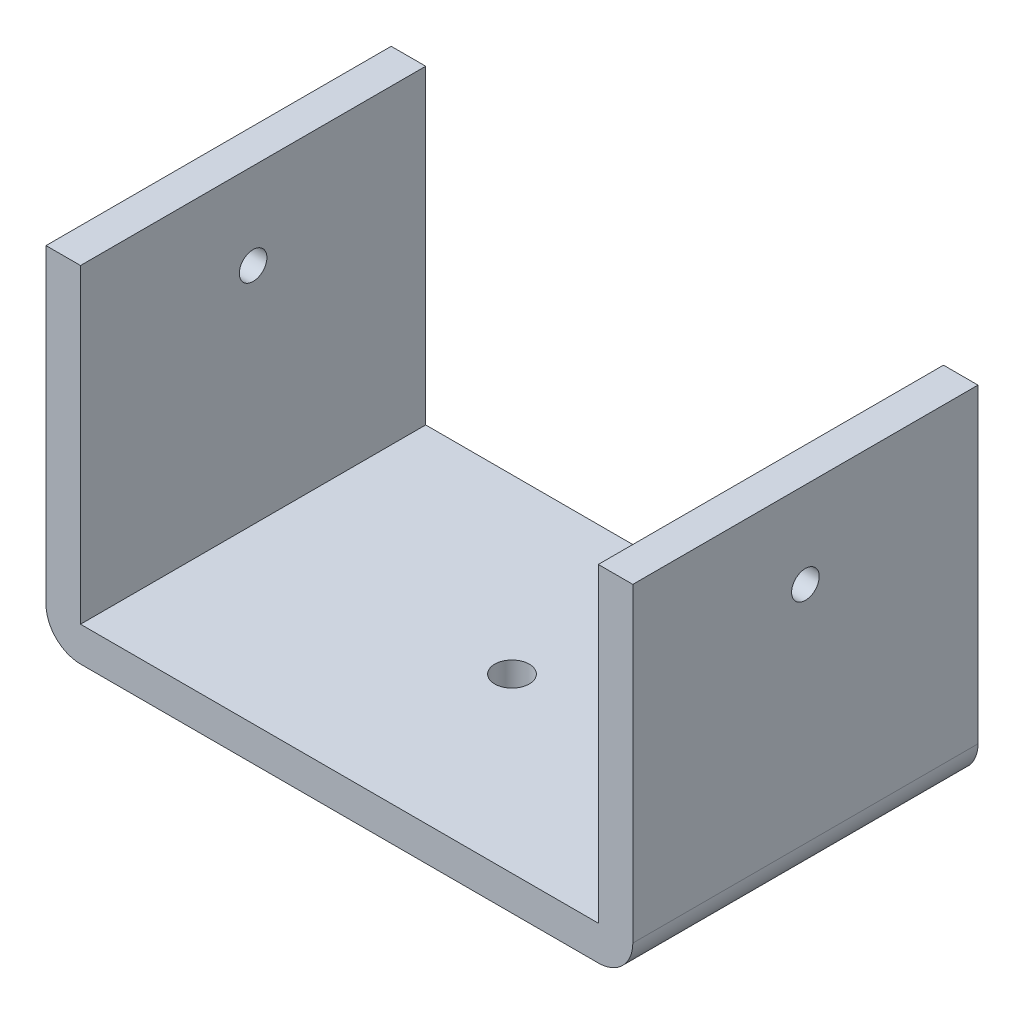
SolidWorks part; units mm, degrees
ref_plane "Front Plane" through (0, 0, 0) normal (0, 0, 1) x (1, 0, 0)
ref_plane "Top Plane" through (0, 0, 0) normal (0, 1, 0) x (1, 0, 0)
ref_plane "Right Plane" through (0, 0, 0) normal (1, 0, 0) x (0, 0, -1)
sketch "Sketch1" plane through (0, 0, 0) normal (0, 0, 1) x (1, 0, 0)
  line L0 (75, -10) -> (75, 140) construction
  line L1 (0, 0) -> (150, 0)
  line L2 (0, 0) -> (0, -10)
  line L3 (0, -10) -> (150, -10)
  line L4 (150, 0) -> (150, -10)
  line L5 (0, -10) -> (-10, -10)
  line L6 (0, -10) -> (0, 90)
  line L7 (0, 90) -> (-10, 90)
  line L8 (-10, -10) -> (-10, 90)
  line L9 (150, 90) -> (160, 90)
  line L10 (160, -10) -> (160, 90)
  line L11 (150, -10) -> (160, -10)
  line L12 (150, -10) -> (150, 90)
  dimension "D1" = 10
  dimension "D2" = 150
  dimension "D3" = 10
  dimension "D4" = 100
extrude "Boss-Extrude1" add sketch "Sketch1" along normal blind 100 contours L0 L3 L4 L1 | L3 L0 L1 L2 | L12 L4 L11 L10 L9 | L8 L5 L2 L6 L7
sketch "Sketch2" plane through (0, 0, 0) normal (0, 1, 0) x (1, 0, 0)
  line L0 (0, 0) -> (150, -100) construction
  circle A0 centre (75, -50) radius 5
extrude "Cut-Extrude1" cut sketch "Sketch2" against normal blind 10
fillet "Fillet1" radius 10 2 edges at (160, -10, 50) (-10, -10, 50)
sketch "Sketch3" plane through (-10, 0, 0) normal (-1, 0, 0) x (0, 0, 1)
  line L0 (0, 0) -> (0, 90) construction
  line L1 (100, 90) -> (0, 90) construction
  circle A0 centre (50, 65) radius 4
  dimension "D1" = 8
  dimension "D2" = 50
  dimension "D3" = 25
extrude "Cut-Extrude2" cut sketch "Sketch3" against normal blind 192
